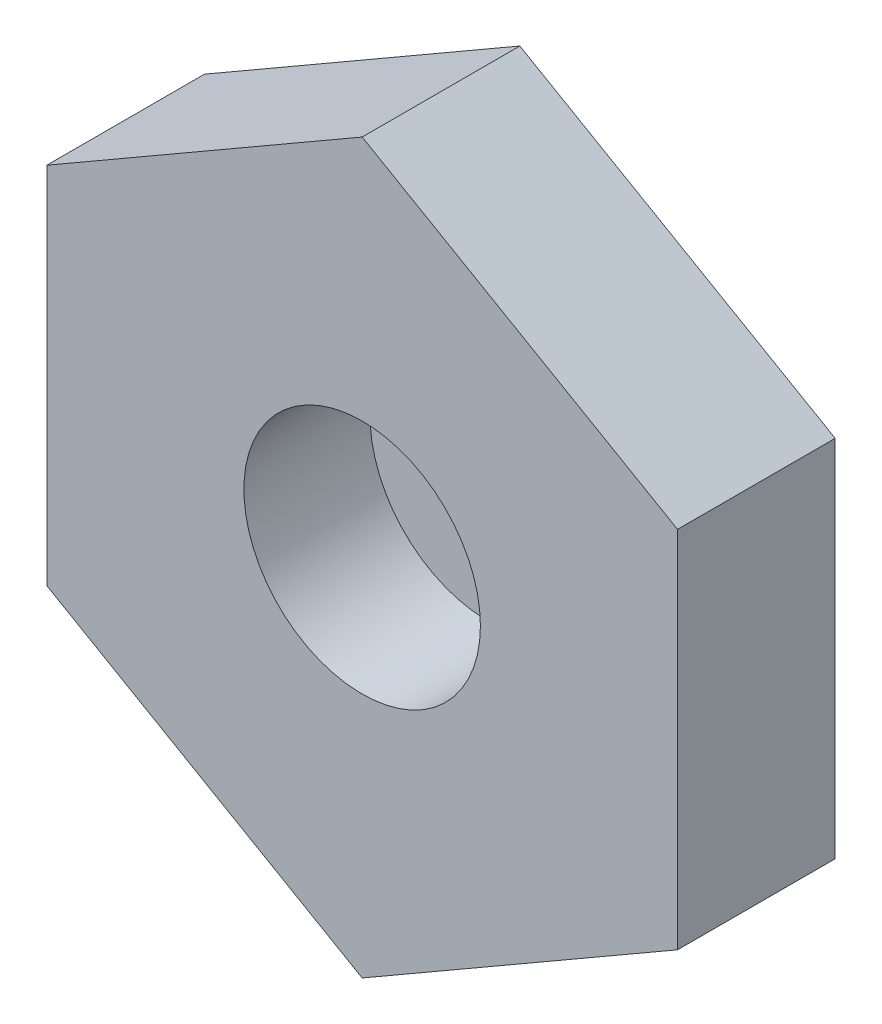
SolidWorks part; units mm, degrees
ref_plane "Front Plane" through (0, 0, 0) normal (0, 0, 1) x (1, 0, 0)
ref_plane "Top Plane" through (0, 0, 0) normal (0, 1, 0) x (1, 0, 0)
ref_plane "Right Plane" through (0, 0, 0) normal (1, 0, 0) x (0, 0, -1)
sketch "Sketch1" plane through (0, 0, 0) normal (0, 0, 1) x (1, 0, 0)
  line L0 (0, 27.588) -> (0, -22.7247) construction
  line L1 (-24.8469, 0) -> (22.1942, 0) construction
  line L3 (0, 9.2376) -> (-8, 4.6188)
  line L4 (-8, 4.6188) -> (-8, -4.6188)
  line L5 (-8, -4.6188) -> (0, -9.2376)
  line L6 (0, -9.2376) -> (8, -4.6188)
  line L7 (8, -4.6188) -> (8, 4.6188)
  line L8 (8, 4.6188) -> (0, 9.2376)
  circle A0 centre (0, 0) radius 8 construction
  dimension "D1" = 16
extrude "Boss-Extrude1" add sketch "Sketch1" along normal blind 4
sketch "Sketch2" plane through (0, 0, 4) normal (0, 0, 1) x (1, 0, 0)
  circle A0 centre (0, 0) radius 3
  dimension "D1" = 6
extrude "Cut-Extrude1" cut sketch "Sketch2" against normal blind 3.2
